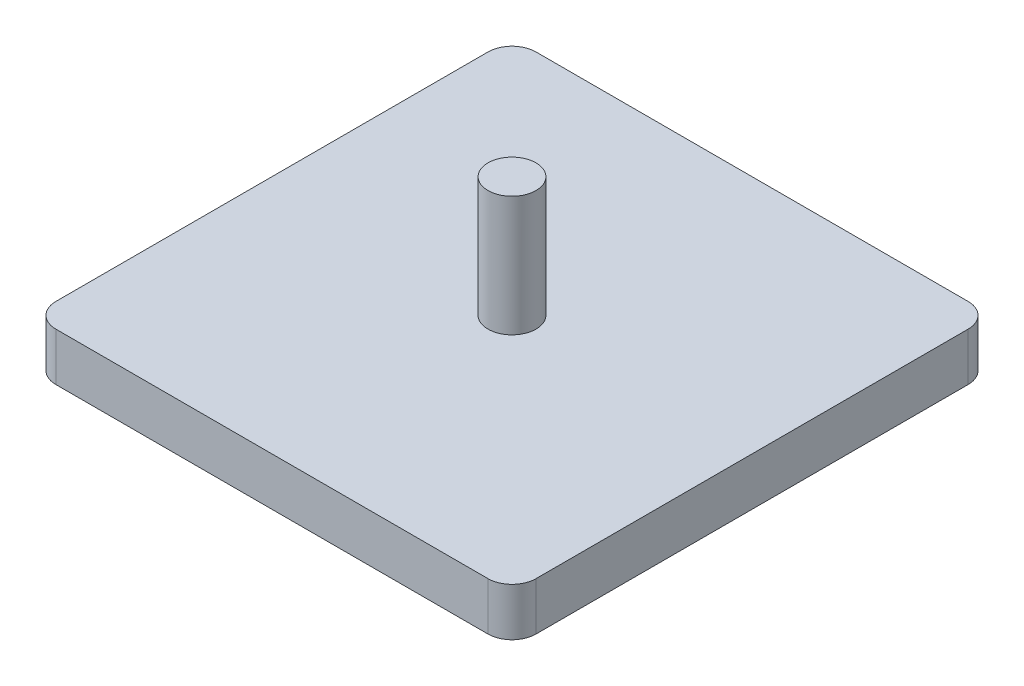
SolidWorks part; units mm, degrees
ref_plane "Front Plane" through (0, 0, 0) normal (0, 0, 1) x (1, 0, 0)
ref_plane "Top Plane" through (0, 0, 0) normal (0, 1, 0) x (1, 0, 0)
ref_plane "Right Plane" through (0, 0, 0) normal (1, 0, 0) x (0, 0, -1)
sketch "Sketch2" plane through (0, 0, 0) normal (0, 1, 0) x (1, 0, 0)
  line L1 (10, 10) -> (-10, 10)
  line L2 (10, 10) -> (10, -10)
  line L3 (10, -10) -> (-10, -10)
  line L4 (-10, 10) -> (-10, -10)
  line L5 (10, 10) -> (-10, -10) construction
  line L6 (10, -10) -> (-10, 10) construction
  point P0 (0, 0)
  dimension "D1" = 20
  dimension "D2" = 20
extrude "Boss-Extrude1" add sketch "Sketch2" along normal blind 2
sketch "Sketch3" plane through (0, 2, 0) normal (0, 1, 0) x (1, 0, 0)
  circle A0 centre (0, 0) radius 1
  dimension "D1" = 2
extrude "Boss-Extrude2" add sketch "Sketch3" along normal blind 5
fillet "Fillet1" radius 1 4 edges at (10, 1, 10) (10, 1, -10) (-10, 1, 10) (-10, 1, -10)
